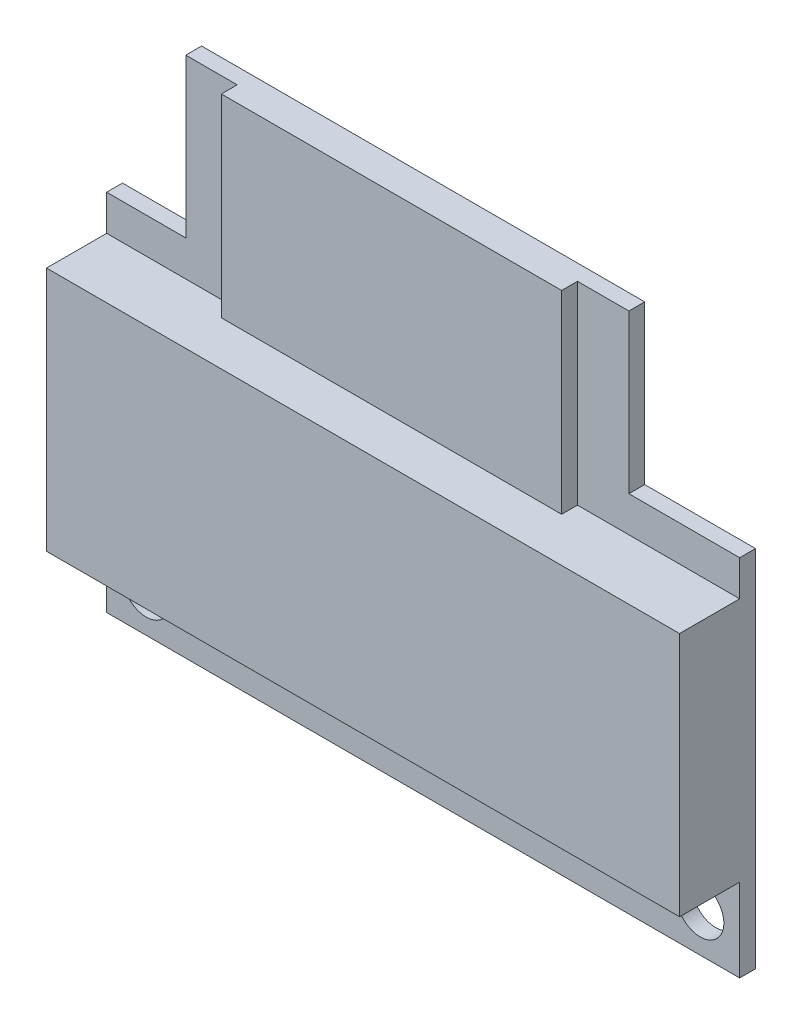
SolidWorks part; units mm, degrees
ref_plane "Alzado" through (0, 0, 0) normal (0, 0, 1) x (1, 0, 0)
ref_plane "Planta" through (0, 0, 0) normal (0, 1, 0) x (1, 0, 0)
ref_plane "Vista lateral" through (0, 0, 0) normal (1, 0, 0) x (0, 0, -1)
sketch "Croquis1" plane through (0, 0, 0) normal (0, 0, 1) x (1, 0, 0)
  line L0 (-88.2703, -7.6575) -> (-88.2703, 15.3425)
  line L1 (-88.2703, 15.3425) -> (-83.2703, 15.3425)
  line L2 (-83.2703, 15.3425) -> (-83.2703, 25.3425)
  line L3 (-83.2703, 25.3425) -> (-55.2703, 25.3425)
  line L4 (-55.2703, 25.3425) -> (-55.2703, 15.3425)
  line L5 (-55.2703, 15.3425) -> (-48.2703, 15.3425)
  line L6 (-48.2703, 15.3425) -> (-48.2703, -7.6575)
  line L7 (-48.2703, -7.6575) -> (-88.2703, -7.6575)
extrude "Saliente-Extruir1" add sketch "Croquis1" along normal blind 1
sketch "Croquis2" plane through (0, 0, 1) normal (0, 0, 1) x (1, 0, 0)
  line L2 (-88.2703, -2.4075) -> (-88.2703, 13.0925)
  line L3 (-88.2703, 13.0925) -> (-80.0203, 13.0925)
  line L4 (-80.0203, 13.0925) -> (-80.0203, 25.3425)
  line L5 (-55.2703, 25.3425) -> (-83.2703, 25.3425) construction
  line L6 (-80.0203, 25.3425) -> (-58.5203, 25.3425)
  line L7 (-88.2703, 15.3425) -> (-88.2703, -7.6575) construction
  line L8 (-58.5203, 25.3425) -> (-58.5203, 13.0925)
  line L9 (-58.5203, 13.0925) -> (-48.2703, 13.0925)
  line L10 (-48.2703, -7.6575) -> (-48.2703, 15.3425) construction
  line L11 (-48.2703, 13.0925) -> (-48.2703, -2.4075)
  line L12 (-48.2703, -2.4075) -> (-88.2703, -2.4075)
  dimension "D2" = 0
  dimension "D3" = 21.5
extrude "Saliente-Extruir2" add sketch "Croquis2" along normal blind 1
sketch "Croquis3" plane through (0, 0, 2) normal (0, 0, 1) x (1, 0, 0)
  line L1 (-88.2703, 13.0925) -> (-48.2703, 13.0925)
  line L2 (-88.2703, 13.0925) -> (-88.2703, -2.4075)
  line L3 (-88.2703, -2.4075) -> (-48.2703, -2.4075)
  line L4 (-48.2703, 13.0925) -> (-48.2703, -2.4075)
extrude "Saliente-Extruir3" add sketch "Croquis3" along normal blind 2.8
sketch "Croquis4" plane through (0, 0, 1) normal (0, 0, 1) x (1, 0, 0)
  line L0 (-88.2703, -7.6575) -> (-48.2703, -7.6575) construction
  line L1 (-88.2703, -2.4075) -> (-88.2703, -7.6575) construction
  circle A0 centre (-85.7703, -5.1575) radius 1.5
  circle A1 centre (-50.7703, -5.1575) radius 1.5
  dimension "D1" = 2.5
  dimension "D2" = 2.5
  dimension "D3" = 2
extrude "Cortar-Extruir1" cut sketch "Croquis4" against normal up to vertex (1 mm away)
